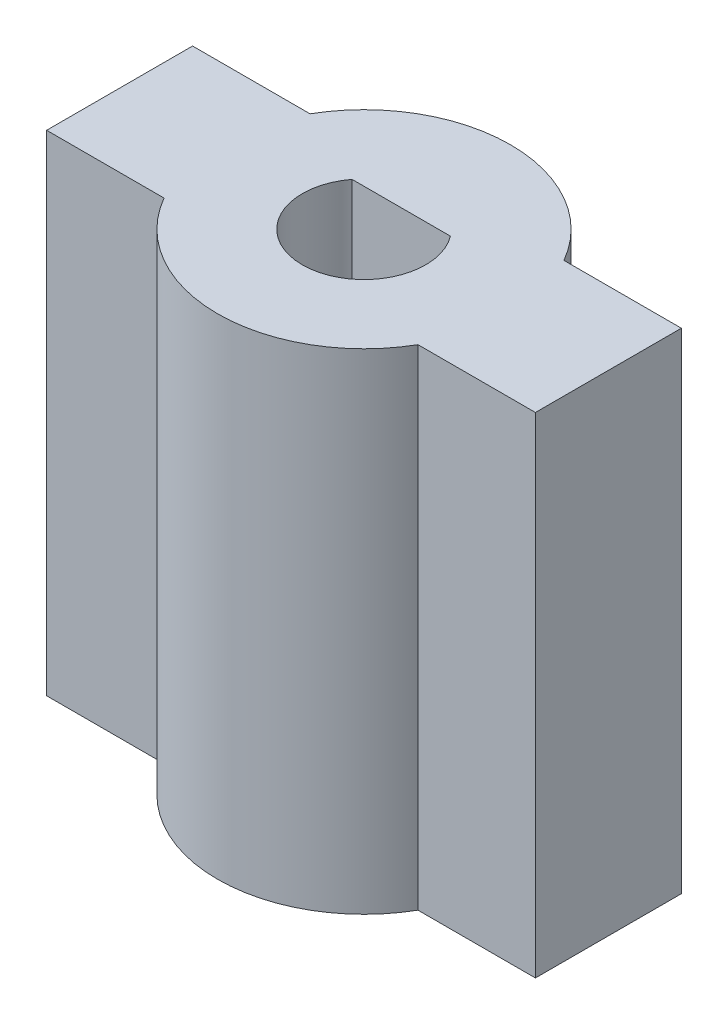
SolidWorks part; units mm, degrees
ref_plane "前视基准面" through (0, 0, 0) normal (0, 0, 1) x (1, 0, 0)
ref_plane "上视基准面" through (0, 0, 0) normal (0, 1, 0) x (1, 0, 0)
ref_plane "右视基准面" through (0, 0, 0) normal (1, 0, 0) x (0, 0, -1)
other "Configuration Table"
sketch "草图1" plane through (0, 0, 0) normal (0, 1, 0) x (1, 0, 0)
  line L1 (9.98, -2.98) -> (5.1846, -2.98)
  line L2 (9.98, -2.98) -> (9.98, 2.98)
  line L3 (9.98, 2.98) -> (5.1846, 2.98)
  line L4 (-9.98, -2.98) -> (-9.98, 2.98)
  line L8 (-5.1846, -2.98) -> (-9.98, -2.98)
  line L9 (-5.1846, 2.98) -> (-9.98, 2.98)
  arc A0 (5.1846, 2.98) -> (-5.1846, 2.98) centre (0, 0) ccw
  arc A1 (-5.1846, -2.98) -> (5.1846, -2.98) centre (0, 0) ccw
  dimension "D1" = 5.96
  dimension "D3" = 11.96
  dimension "D2" = 19.96
extrude "凸台-拉伸3" add sketch "草图1" along normal blind 20
sketch "草图5" plane through (0, 20, 0) normal (0, 1, 0) x (1, 0, 0)
  line L0 (0, 1003.9261) -> (0, 5.98) construction
  line L1 (-2.01, 1.52) -> (2.01, 1.52)
  line L2 (0, 1.52) -> (0, -1000.0833) construction
  line L6 (-5.1846, 2.98) -> (-9.98, 2.98)
  line L7 (-9.98, 2.98) -> (-9.98, -2.98)
  line L8 (-9.98, -2.98) -> (-5.1846, -2.98)
  line L9 (5.1846, -2.98) -> (9.98, -2.98)
  line L10 (9.98, -2.98) -> (9.98, 2.98)
  line L11 (9.98, 2.98) -> (5.1846, 2.98)
  line L12 (-5.1846, 2.98) -> (-9.98, 2.98)
  line L13 (-9.98, 2.98) -> (-9.98, -2.98)
  line L14 (-9.98, -2.98) -> (-5.1846, -2.98)
  line L15 (5.1846, -2.98) -> (9.98, -2.98)
  line L16 (9.98, -2.98) -> (9.98, 2.98)
  line L17 (9.98, 2.98) -> (5.1846, 2.98)
  arc A0 (-2.01, 1.52) -> (2.01, 1.52) centre (0, 0) ccw
  arc A2 (5.1846, 2.98) -> (-5.1846, 2.98) centre (0, 0) ccw
  arc A3 (-5.1846, -2.98) -> (5.1846, -2.98) centre (0, 0) ccw
  arc A4 (5.1846, 2.98) -> (-5.1846, 2.98) centre (0, 0) ccw
  arc A5 (-5.1846, -2.98) -> (5.1846, -2.98) centre (0, 0) ccw
  point P9 (0, 2.52)
  dimension "D2" = 5.04
  dimension "D3" = 1.52
  dimension "D1" = 0
extrude "切除-拉伸4" cut sketch "草图5" against normal blind 15 contours A0 L1
sketch "草图6" plane through (0, 0, 0) normal (0, -1, 0) x (1, 0, 0)
  circle A0 centre (0, 0) radius 2.52
  dimension "D1" = 5.04
extrude "切除-拉伸5" cut sketch "草图6" against normal blind 5
